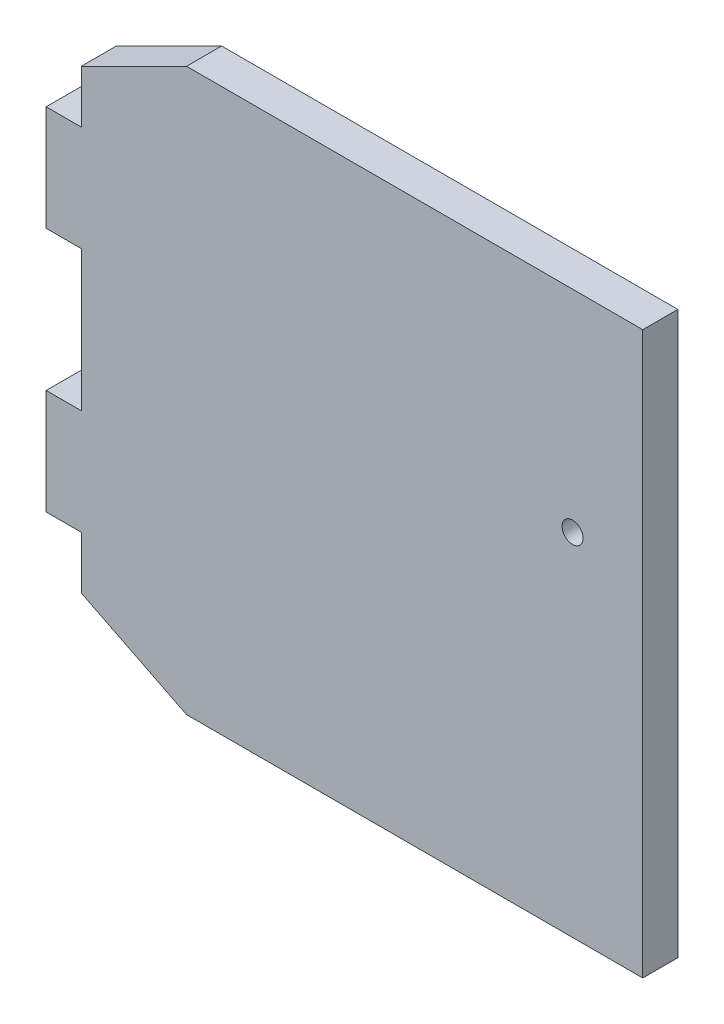
SolidWorks part; units mm, degrees
material "PVC Rigid"
ref_plane "Front Plane" through (0, 0, 0) normal (0, 0, 1) x (1, 0, 0)
ref_plane "Top Plane" through (0, 0, 0) normal (0, 1, 0) x (1, 0, 0)
ref_plane "Right Plane" through (0, 0, 0) normal (1, 0, 0) x (0, 0, -1)
sketch "Sketch1" plane through (0, 0, 0) normal (0, 0, 1) x (1, 0, 0)
  line L0 (0, 31.7838) -> (10, 31.7838)
  line L1 (-40, 31.7838) -> (0, 31.7838)
  line L2 (-40, 31.7838) -> (-40, -48.2162)
  line L3 (-40, -48.2162) -> (40, -48.2162)
  line L4 (40, 21.7838) -> (40, -48.2162)
  line L6 (40, 21.7838) -> (40, 31.7838)
  line L7 (40, 31.7838) -> (10, 31.7838)
  dimension "D1" = 80
  dimension "D2" = 80
  dimension "D3" = 10
  dimension "D4" = 30
  dimension "D5" = 70
extrude "Boss-Extrude1" add sketch "Sketch1" along normal blind 5
sketch "Sketch3" plane through (-40, 0, 0) normal (-1, 0, 0) x (0, 0, 1)
  line L0 (0, 31.7838) -> (0, -48.2162) construction
  line L1 (0, 16.7838) -> (5, 16.7838)
  line L2 (0, 16.7838) -> (0, 1.7838)
  line L3 (0, 1.7838) -> (5, 1.7838)
  line L4 (5, 16.7838) -> (5, 1.7838)
  line L5 (5, 31.7838) -> (5, -48.2162) construction
  line L6 (5, -48.2162) -> (0, -48.2162) construction
  line L7 (0, -18.2162) -> (5, -18.2162)
  line L8 (0, -18.2162) -> (0, -33.2162)
  line L9 (0, -33.2162) -> (5, -33.2162)
  line L10 (5, -18.2162) -> (5, -33.2162)
  dimension "D1" = 15
  dimension "D2" = 15
  dimension "D3" = 20
  dimension "D4" = 15
extrude "Boss-Extrude2" add sketch "Sketch3" along normal blind 5
sketch "Sketch4" plane through (0, 0, 5) normal (0, 0, 1) x (1, 0, 0)
  line L0 (-40, 31.7838) -> (-25, 31.7838)
  line L1 (40, 31.7838) -> (-40, 31.7838) construction
  line L2 (-25, 31.7838) -> (-40, 24.2838)
  line L3 (-40, 31.7838) -> (-40, 16.7838) construction
  line L4 (-40, 24.2838) -> (-40, 31.7838)
  line L5 (-40, -48.2162) -> (-40, -40.7162)
  line L6 (-40, -33.2162) -> (-40, -48.2162) construction
  line L7 (-40, -40.7162) -> (-25, -48.2162)
  line L8 (-40, -48.2162) -> (40, -48.2162) construction
  line L9 (-25, -48.2162) -> (-40, -48.2162)
  dimension "D1" = 15
  dimension "D2" = 15
extrude "Cut-Extrude2" cut sketch "Sketch4" against normal blind 5
sketch "Sketch5" plane through (0, 0, 5) normal (0, 0, 1) x (1, 0, 0)
  line L0 (40, -48.2162) -> (40, 31.7838) construction
  line L1 (-25, -48.2162) -> (40, -48.2162) construction
  circle A0 centre (30, 1.7838) radius 1.5
  dimension "D1" = 3
  dimension "D2" = 10
  dimension "D3" = 50
extrude "Cut-Extrude3" cut sketch "Sketch5" against normal blind 5
